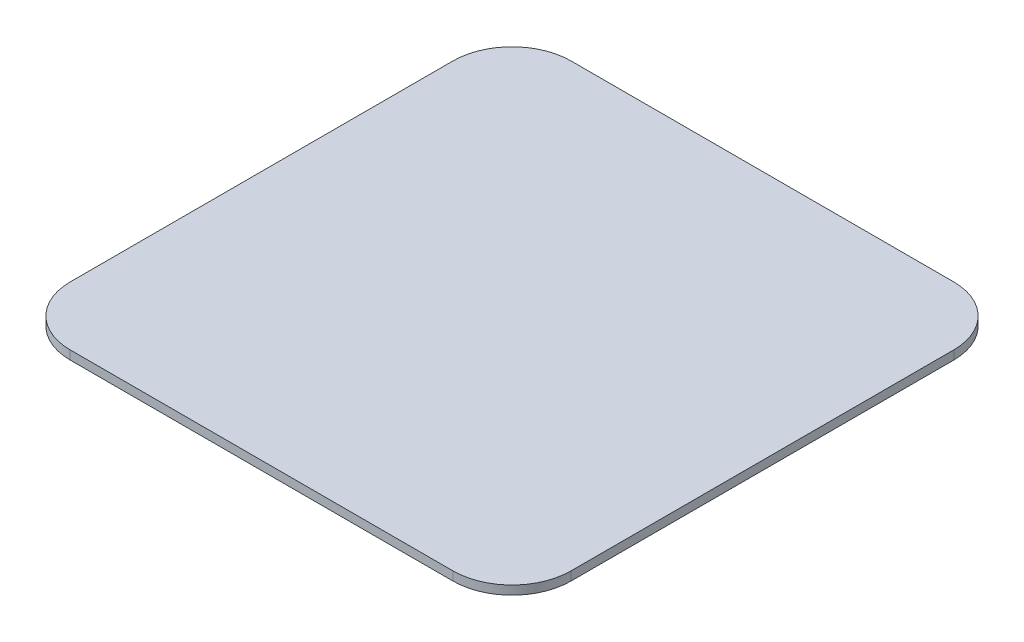
SolidWorks part; units mm, degrees
ref_plane "Front Plane" through (0, 0, 0) normal (0, 0, 1) x (1, 0, 0)
ref_plane "Top Plane" through (0, 0, 0) normal (0, 1, 0) x (1, 0, 0)
ref_plane "Right Plane" through (0, 0, 0) normal (1, 0, 0) x (0, 0, -1)
sketch "Sketch1" plane through (0, 0, 0) normal (0, 1, 0) x (1, 0, 0)
  line L1 (-85, -85) -> (85, -85)
  line L2 (-85, -85) -> (-85, 85)
  line L3 (-85, 85) -> (85, 85)
  line L4 (85, -85) -> (85, 85)
  line L5 (-85, -85) -> (85, 85) construction
  line L6 (-85, 85) -> (85, -85) construction
  point P0 (0, 0)
  dimension "D1" = 170
  dimension "D2" = 170
extrude "Boss-Extrude4" add sketch "Sketch1" along normal blind 3
fillet "Fillet1" radius 20 4 edges at (-85, 1.5, 85) (-85, 1.5, -85) (85, 1.5, -85) (85, 1.5, 85)
